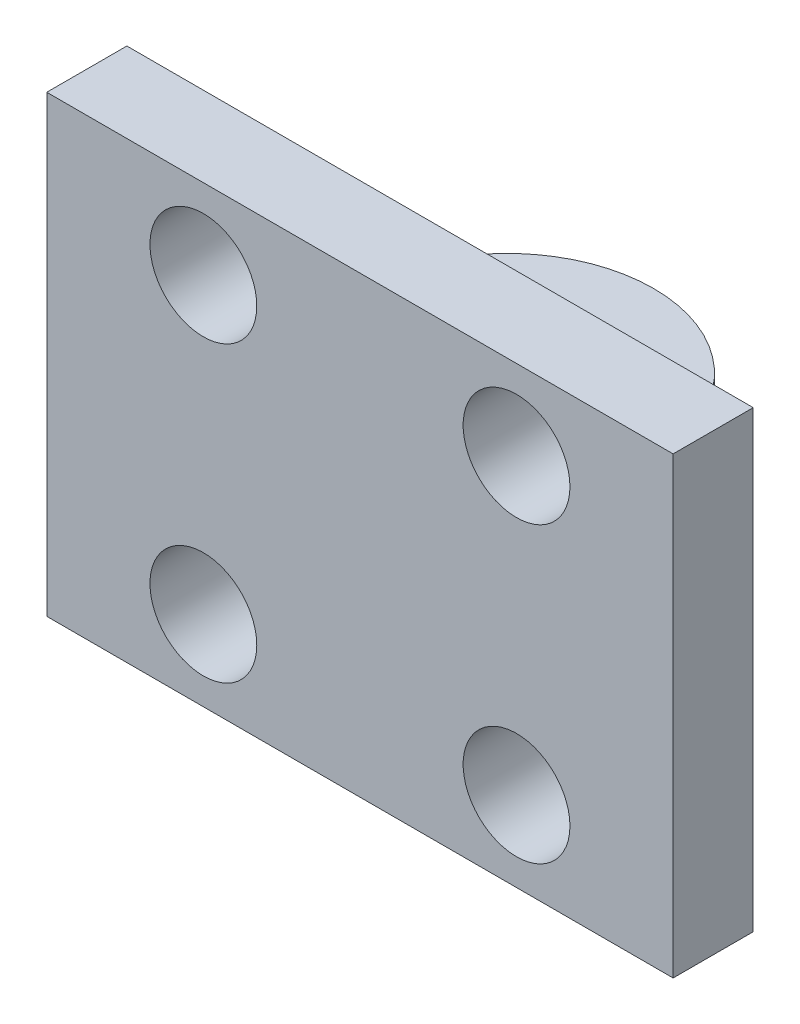
SolidWorks part; units mm, degrees
ref_plane "Front Plane" through (0, 0, 0) normal (0, 0, 1) x (1, 0, 0)
ref_plane "Top Plane" through (0, 0, 0) normal (0, 1, 0) x (1, 0, 0)
ref_plane "Right Plane" through (0, 0, 0) normal (1, 0, 0) x (0, 0, -1)
sketch "Sketch1" plane through (0, 0, 0) normal (0, 1, 0) x (1, 0, 0)
  line L0 (5.5, 0) -> (11.7297, -2.5)
  line L1 (-25.742, -2.5) -> (25.742, -2.5)
  line L2 (0, -2.5) -> (0, -5.5)
  line L3 (-25.742, -5.5) -> (25.742, -5.5)
  line L4 (25.742, -2.5) -> (25.742, -5.5)
  line L5 (-25.742, -2.5) -> (-25.742, -5.5)
  line L6 (-5.5, 0) -> (-11.7297, -2.5)
  circle A0 centre (0, 0) radius 2.5
  circle A1 centre (0, 0) radius 5.5
  dimension "D1" = 3
extrude "Boss-Extrude1" add sketch "Sketch1" along normal blind 5 contours L1 A1 A0 | L2 A1 L1 | A1 L3 L4 L1 | A1 L1 L0 | L1 A1 L2 | A1 L6 L1 | A1 L1 L5 L3
sketch "Sketch2" plane through (0, 0, 2.5) normal (0, 0, -1) x (-1, 0, 0)
  line L0 (-11.7297, 5) -> (-11.7297, 0) construction
  line L1 (-11.7297, 2.5) -> (-21.7297, 2.5)
  line L2 (0, 5) -> (0, 4.2863)
  line L3 (5.5, 5) -> (-5.5, 5) construction
  line L4 (11.7297, 0) -> (25.742, 0) construction
  line L5 (25.742, 0) -> (25.742, 5) construction
  line L6 (25.742, 5) -> (11.7297, 5) construction
  line L7 (11.7297, 5) -> (11.7297, 0) construction
  line L8 (-25.742, 0) -> (-11.7297, 0) construction
  line L9 (-11.7297, 0) -> (-11.7297, 5) construction
  line L10 (-11.7297, 5) -> (-25.742, 5) construction
  line L11 (-25.742, 5) -> (-25.742, 0) construction
  line L12 (11.7297, 0) -> (25.742, 0)
  line L13 (25.742, 0) -> (25.742, 5)
  line L14 (25.742, 5) -> (11.7297, 5)
  line L15 (11.7297, 5) -> (11.7297, 0)
  line L16 (-25.742, 0) -> (-11.7297, 0)
  line L17 (-11.7297, 0) -> (-11.7297, 5)
  line L18 (-11.7297, 5) -> (-25.742, 5)
  line L19 (-25.742, 5) -> (-25.742, 0)
  line L20 (-21.7297, 5) -> (-21.7297, 0)
  line L21 (21.7297, 5) -> (21.7297, 0)
  line L22 (11.7297, 0) -> (11.7297, 5)
  line L23 (11.7297, 2.5) -> (21.7297, 2.5)
  circle A0 centre (-16.7297, 2.5) radius 2
  circle A1 centre (16.7297, 2.5) radius 2
  line M5 (25.742, 0) -> (25.742, 5)
  line M6 (25.742, 5) -> (11.7297, 5)
extrude "Cut-Extrude1" cut sketch "Sketch2" against normal blind 5 contours L20 L18 L19 L16 | L21 L12 M6 M5 | A1 | A0
sketch "Sketch5" plane through (0, 0, 2.5) normal (0, 0, -1) x (-1, 0, 0)
  line L4 (-11.7297, 5) -> (-21.7297, 5)
  line L5 (-21.7297, 5) -> (-21.7297, 0)
  line L6 (-21.7297, 0) -> (-11.7297, 0)
  line L7 (-11.7297, 0) -> (-11.7297, 5)
  line L8 (-11.7297, 5) -> (-21.7297, 5)
  line L9 (-21.7297, 5) -> (-21.7297, 0)
  line L10 (-21.7297, 0) -> (-11.7297, 0)
  line L11 (-11.7297, 0) -> (-11.7297, 5)
  line L12 (21.7297, 0) -> (21.7297, 5)
  line L13 (21.7297, 5) -> (11.7297, 5)
  line L14 (11.7297, 5) -> (11.7297, 0)
  line L15 (11.7297, 0) -> (21.7297, 0)
  line L16 (21.7297, 0) -> (21.7297, 5)
  line L17 (21.7297, 5) -> (11.7297, 5)
  line L18 (11.7297, 5) -> (11.7297, 0)
  line L19 (11.7297, 0) -> (21.7297, 0)
  dimension "D1" = 0
  dimension "D2" = 0
extrude "Cut-Extrude2" cut sketch "Sketch5" against normal blind 5
sketch "Sketch6" plane through (0, 0, 5.5) normal (0, 0, 1) x (1, 0, 0)
  line L0 (0, 11) -> (0, 5)
  line L1 (-11.7297, 5) -> (11.7297, 5)
  line L2 (-11.7297, 5) -> (-11.7297, 11)
  line L3 (-11.7297, 11) -> (11.7297, 11)
  line L4 (11.7297, 5) -> (11.7297, 11)
  line L5 (-11.7297, 8) -> (0, 8)
  line L6 (-11.7297, 2.5) -> (-9.7543, 2.5)
  line L7 (-11.7297, 5) -> (-11.7297, 0) construction
  line L8 (-11.7297, -3) -> (0, -3)
  line L9 (11.7297, 0) -> (11.7297, -6)
  line L10 (-11.7297, -6) -> (11.7297, -6)
  line L11 (-11.7297, 0) -> (-11.7297, -6)
  line L12 (-11.7297, 0) -> (11.7297, 0)
  line L13 (0, -6) -> (0, 0)
  circle A0 centre (-5.8648, 8) radius 2
  circle A1 centre (5.8648, 8) radius 2
  circle A2 centre (5.8648, -3) radius 2
  circle A3 centre (-5.8648, -3) radius 2
  line M5 (-11.7297, 0) -> (11.7297, 0)
  line M7 (11.7297, 5) -> (-11.7297, 5)
extrude "Boss-Extrude4" add sketch "Sketch6" against normal blind 3 contours L4 L3 L0 A1 M7 | L13 L10 L9 L12 A2 | A0 L5 L2 L0 M7 | A0 L5 L0 L3 L2 | L8 A3 L13 L11 M5 | L8 A3 L11 L10 L13
